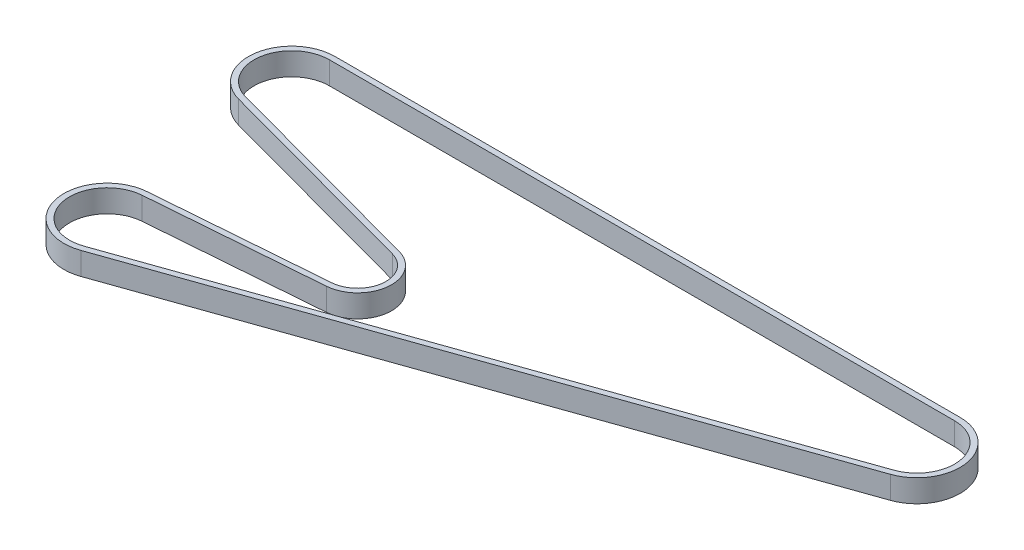
SolidWorks part; units mm, degrees
material "橡胶"
ref_plane "前视基准面" through (0, 0, 0) normal (0, 0, 1) x (1, 0, 0)
ref_plane "上视基准面" through (0, 0, 0) normal (0, 1, 0) x (1, 0, 0)
ref_plane "右视基准面" through (0, 0, 0) normal (1, 0, 0) x (0, 0, -1)
sketch "草图1" plane through (0, 0, 0) normal (0, 1, 0) x (1, 0, 0)
  circle A0 centre (-102, 67) radius 20 construction
  circle A1 centre (0, 0) radius 18 construction
  circle A2 centre (-88, -45) radius 20 construction
  circle A3 centre (230, 67) radius 20 construction
  dimension "D1" = 40
  dimension "D6" = 36
  dimension "D2" = 112
  dimension "D3" = 14
  dimension "D4" = 67
  dimension "D5" = 102
  dimension "D7" = 332
sketch "草图2" plane through (0, 0, 0) normal (0, 1, 0) x (1, 0, 0)
  line L0 (-102, 87) -> (230, 87)
  line L1 (-107.2293, 47.6957) -> (4.7063, 17.3738)
  line L2 (1.4038, -17.9452) -> (-89.5598, -25.0609)
  line L3 (-81.356, -63.8642) -> (236.644, 48.1358)
  arc A0 (-102, 87) -> (-107.2293, 47.6957) centre (-102, 67) ccw
  arc A1 (1.4038, -17.9452) -> (4.7063, 17.3738) centre (0, 0) ccw
  arc A2 (-89.5598, -25.0609) -> (-81.356, -63.8642) centre (-88, -45) ccw
  arc A3 (236.644, 48.1358) -> (230, 87) centre (230, 67) ccw
  circle A4 centre (0, 0) radius 18 construction
  circle A5 centre (-102, 67) radius 20 construction
  circle A6 centre (-88, -45) radius 20 construction
extrude "拉伸-薄壁1" add sketch "草图2" along normal blind 12 thin thin type one direction wall 3
